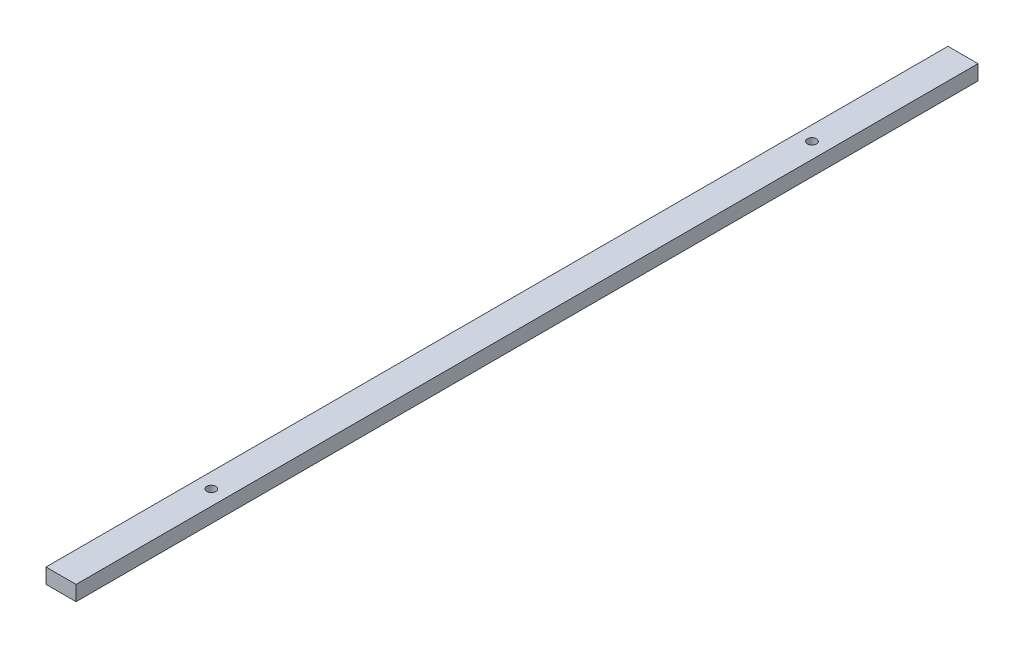
SolidWorks part; units mm, degrees
ref_plane "Front Plane" through (0, 0, 0) normal (0, 0, 1) x (1, 0, 0)
ref_plane "Top Plane" through (0, 0, 0) normal (0, 1, 0) x (1, 0, 0)
ref_plane "Right Plane" through (0, 0, 0) normal (1, 0, 0) x (0, 0, -1)
sketch "Sketch1" plane through (0, 0, 0) normal (0, 0, 1) x (1, 0, 0)
  line L1 (-4.7679, 0.3797) -> (5.2321, 0.3797)
  line L2 (-4.7679, 0.3797) -> (-4.7679, -4.6203)
  line L3 (-4.7679, -4.6203) -> (5.2321, -4.6203)
  line L4 (5.2321, 0.3797) -> (5.2321, -4.6203)
  dimension "D1" = 10
  dimension "D2" = 5
extrude "Boss-Extrude1" add sketch "Sketch1" along normal blind 300
sketch "Sketch2" plane through (0, 0.3797, 0) normal (0, 1, 0) x (1, 0, 0)
  line L0 (0, 0) -> (0, -50)
  line L1 (0.2321, -300) -> (0.2321, -250)
  line L2 (5.2321, -300) -> (-4.7679, -300) construction
  circle A0 centre (0.2321, -250) radius 1.5
  circle A1 centre (0, -50) radius 1.5
  dimension "D3" = 3
  dimension "D4" = 3
  dimension "D1" = 50
  dimension "D2" = 50
extrude "Cut-Extrude1" cut sketch "Sketch2" against normal through all both and the other way through all
